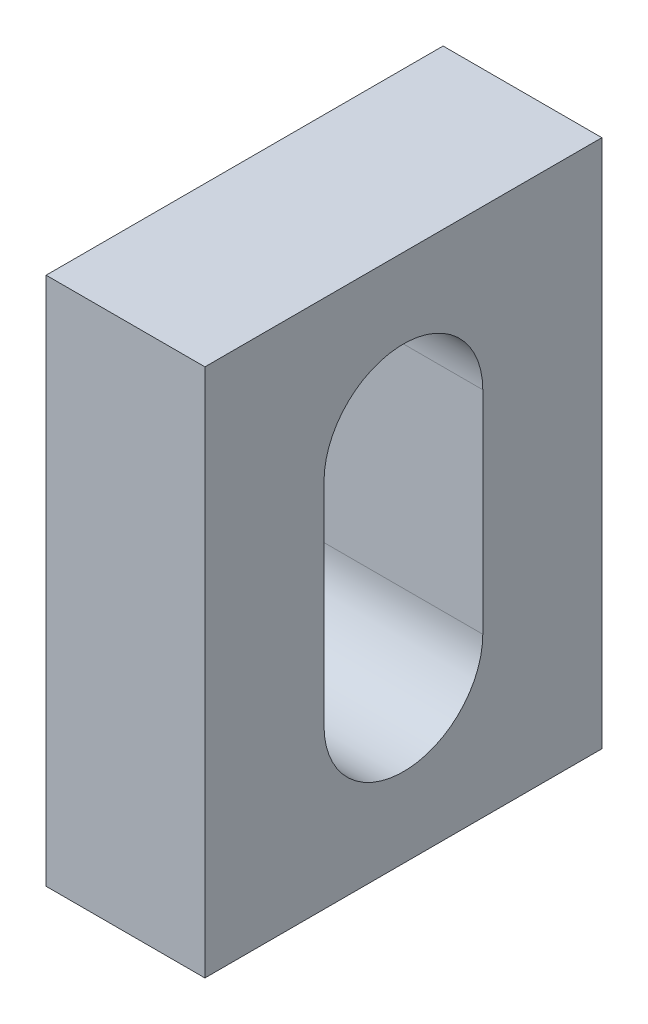
SolidWorks part; units mm, degrees
material "Acrilico TEC"
ref_plane "Front Plane" through (0, 0, 0) normal (0, 0, 1) x (1, 0, 0)
ref_plane "Top Plane" through (0, 0, 0) normal (0, 1, 0) x (1, 0, 0)
ref_plane "Right Plane" through (0, 0, 0) normal (1, 0, 0) x (0, 0, -1)
sketch "Sketch1" plane through (0, 0, 0) normal (1, 0, 0) x (0, 0, -1)
  line L0 (7.5, 6) -> (7.5, 14) construction
  line L1 (0, 0) -> (15, 0)
  line L2 (0, 0) -> (0, 20)
  line L3 (0, 20) -> (15, 20)
  line L4 (15, 0) -> (15, 20)
  line L5 (4.5, 6) -> (4.5, 14)
  line L6 (10.5, 6) -> (10.5, 14)
  arc A0 (4.5, 6) -> (10.5, 6) centre (7.5, 6) ccw
  arc A1 (10.5, 14) -> (4.5, 14) centre (7.5, 14) ccw
  point P5 (7.5, 0)
  point P8 (7.5, 10)
  dimension "D4" = 3
  dimension "D1" = 15
  dimension "D2" = 20
  dimension "D3" = 6
  dimension "D5" = 8
  dimension "D6" = 7.5
extrude "Boss-Extrude1" add sketch "Sketch1" along normal blind 6
